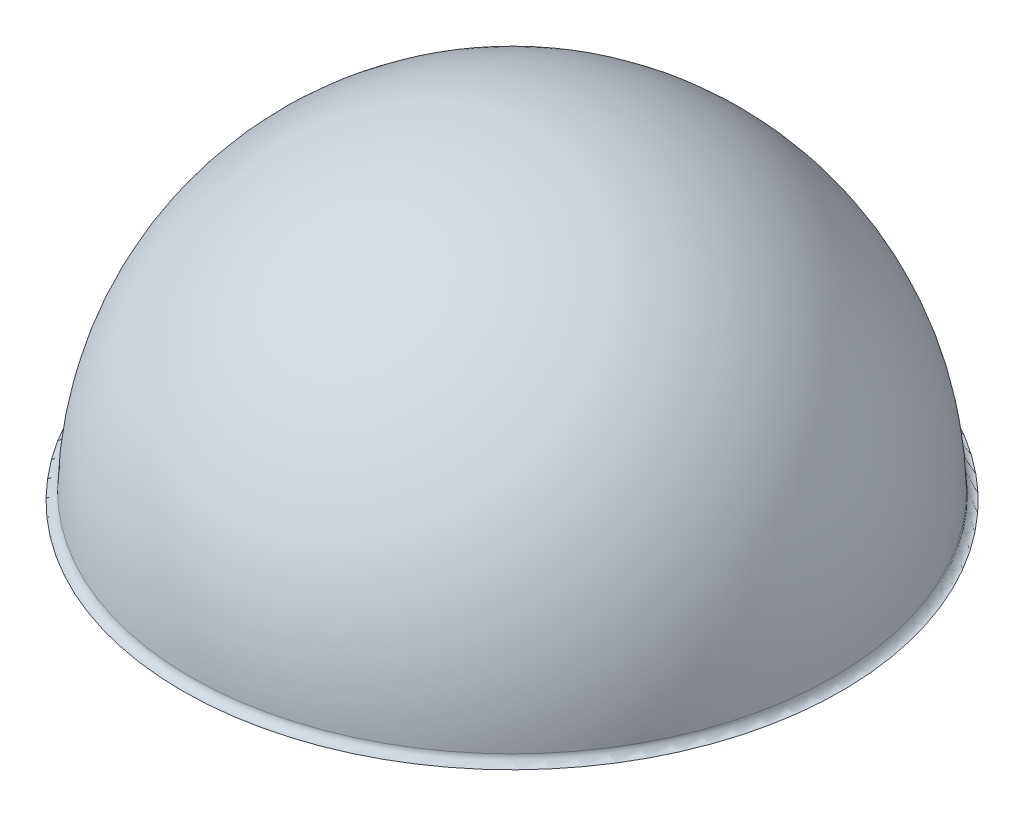
SolidWorks part; units mm, degrees
material "ABS PC"
ref_plane "Front Plane" through (0, 0, 0) normal (0, 0, 1) x (1, 0, 0)
ref_plane "Top Plane" through (0, 0, 0) normal (0, 1, 0) x (1, 0, 0)
ref_plane "Right Plane" through (0, 0, 0) normal (1, 0, 0) x (0, 0, -1)
sketch "Sketch1" plane through (0, 0, 0) normal (0, 0, 1) x (1, 0, 0)
  line L0 (1.25, 1.25) -> (1.25, 0)
  line L4 (2.5, 0) -> (2.5, 0.0269) construction
  line L5 (1.25, 0) -> (2.5315, 0)
  arc A2 (2.4996, 0.0312) -> (2.5315, 0) centre (2.5315, 0.0319) ccw
  arc A3 (2.4996, 0.0312) -> (1.25, 1.25) centre (1.25, 0) ccw
  point P11 (2.5315, 0)
revolve "Revolve2" add sketch "Sketch1" angle 360 about L0
shell "Shell1" thickness 0.1
